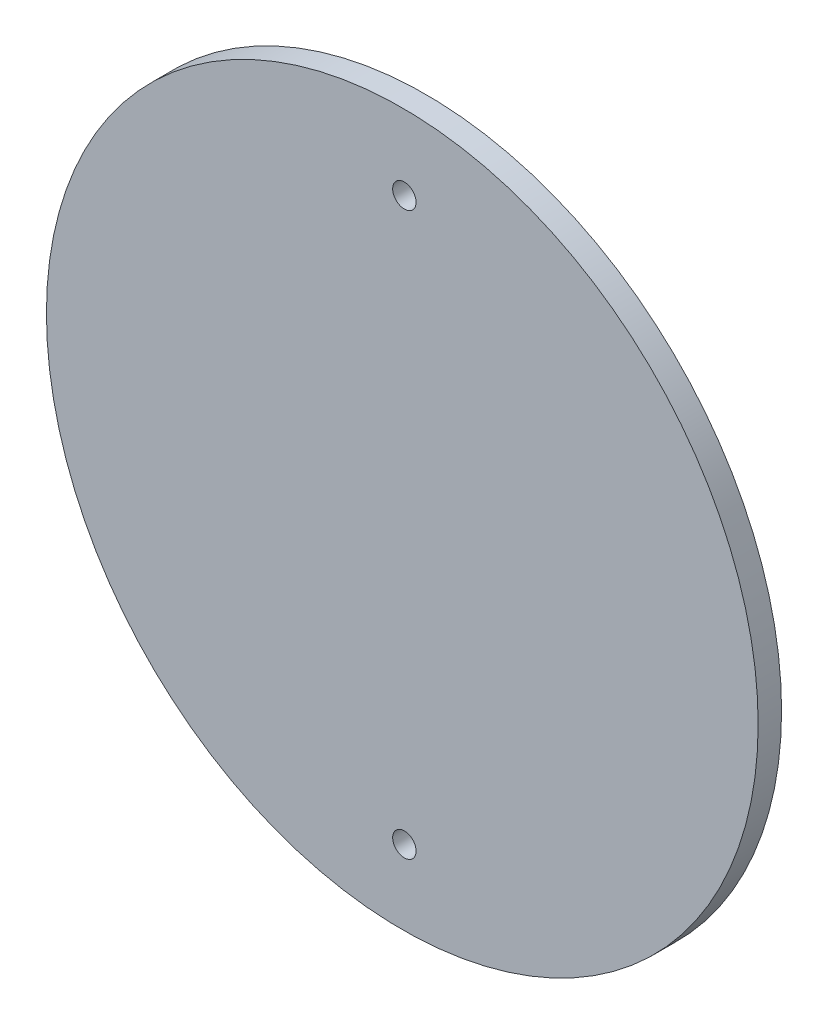
SolidWorks part; units mm, degrees
ref_plane "Front Plane" through (0, 0, 0) normal (0, 0, 1) x (1, 0, 0)
ref_plane "Top Plane" through (0, 0, 0) normal (0, 1, 0) x (1, 0, 0)
ref_plane "Right Plane" through (0, 0, 0) normal (1, 0, 0) x (0, 0, -1)
sketch "Sketch1" plane through (0, 0, 0) normal (0, 0, 1) x (1, 0, 0)
  circle A1 centre (-94.397, 74.705) radius 76
  dimension "D2" = 152
extrude "Boss-Extrude1" add sketch "Sketch1" along normal blind 5
sketch "Sketch2" plane through (0, 0, 5) normal (0, 0, 1) x (1, 0, 0)
  circle A0 centre (-93.9534, 134.705) radius 2.5
  circle A1 centre (-94.397, 74.705) radius 76 construction
  circle A2 centre (-93.9534, 14.705) radius 2.5
  dimension "D1" = 5
  dimension "D3" = 60
  dimension "D2" = 60
extrude "Cut-Extrude1" cut sketch "Sketch2" against normal blind 10
